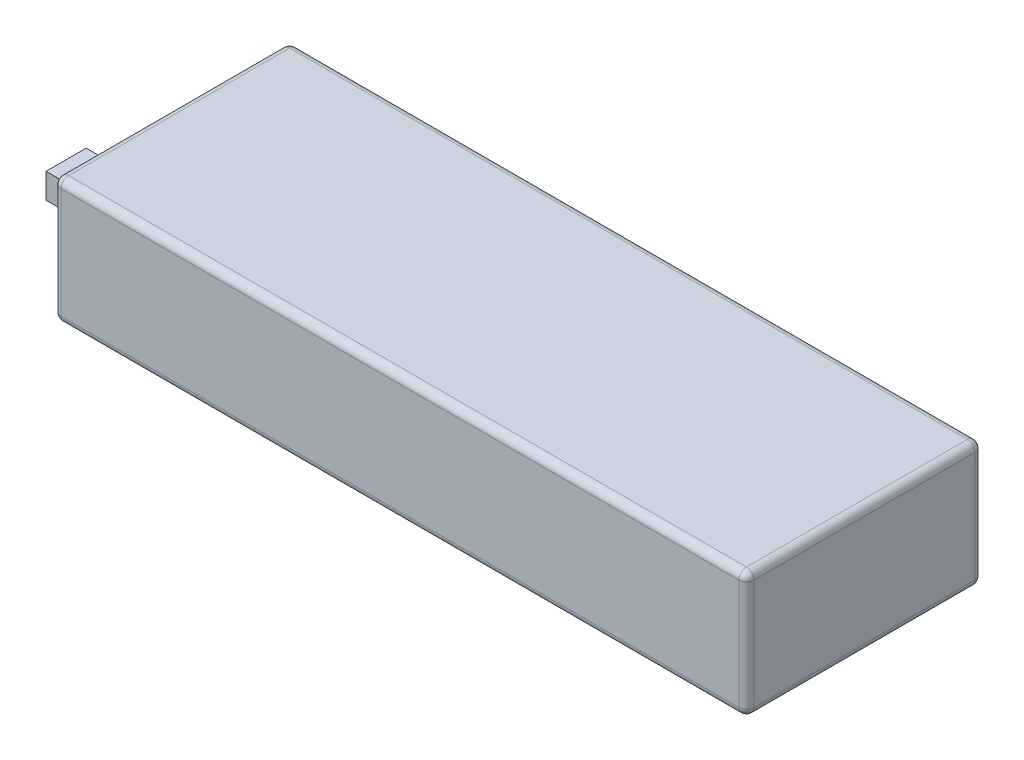
SolidWorks part; units mm, degrees
ref_plane "Front Plane" through (0, 0, 0) normal (0, 0, 1) x (1, 0, 0)
ref_plane "Top Plane" through (0, 0, 0) normal (0, 1, 0) x (1, 0, 0)
ref_plane "Right Plane" through (0, 0, 0) normal (1, 0, 0) x (0, 0, -1)
sketch "Sketch1" plane through (0, 0, 0) normal (0, 1, 0) x (1, 0, 0)
  line L1 (-69, -23.5) -> (69, -23.5)
  line L2 (-69, -23.5) -> (-69, 23.5)
  line L3 (-69, 23.5) -> (69, 23.5)
  line L4 (69, -23.5) -> (69, 23.5)
  line L5 (-69, -23.5) -> (69, 23.5) construction
  line L6 (-69, 23.5) -> (69, -23.5) construction
  point P0 (0, 0)
  dimension "D1" = 138
  dimension "D2" = 47
extrude "Boss-Extrude1" add sketch "Sketch1" along normal mid plane 25
fillet "Fillet1" radius 1.5 12 edges at (-69, -12.5, 0) (-69, 0, -23.5) (0, -12.5, -23.5) (69, 0, -23.5) (69, -12.5, 0) (-69, 0, 23.5) (69, 0, 23.5) (0, -12.5, 23.5) (0, 12.5, 23.5) (-69, 12.5, 0) (0, 12.5, -23.5) (69, 12.5, 0)
sketch "Sketch2" plane through (-69, 0, 0) normal (-1, 0, 0) x (0, 0, 1)
  line L0 (22, -11) -> (22, 11) construction
  line L1 (20, 4) -> (12, 4)
  line L2 (20, 4) -> (20, 9)
  line L3 (20, 9) -> (12, 9)
  line L4 (12, 4) -> (12, 9)
  line L5 (20, 4) -> (12, 9) construction
  line L6 (20, 9) -> (12, 4) construction
  line L7 (22, 11) -> (-22, 11) construction
  point P0 (16, 6.5)
  dimension "D1" = 8
  dimension "D2" = 5
  dimension "D3" = 2
  dimension "D4" = 2
extrude "Boss-Extrude2" add sketch "Sketch2" along normal blind 5
